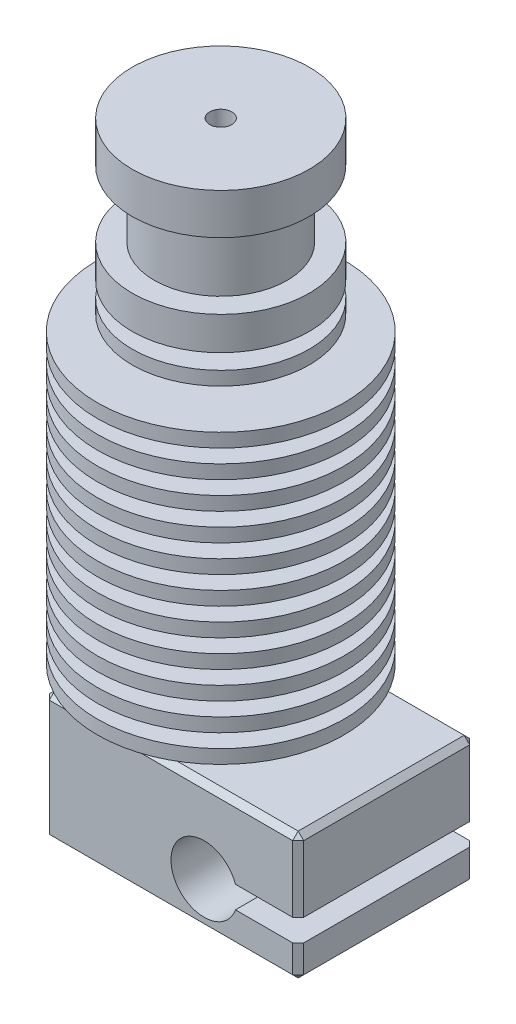
SolidWorks part; units mm, degrees
material "6063-T83"
ref_plane "Front Plane" through (0, 0, 0) normal (0, 0, 1) x (1, 0, 0)
ref_plane "Top Plane" through (0, 0, 0) normal (0, 1, 0) x (1, 0, 0)
ref_plane "Right Plane" through (0, 0, 0) normal (1, 0, 0) x (0, 0, -1)
sketch "Sketch1" plane through (0, 0, 0) normal (0, 0, 1) x (1, 0, 0)
  line L0 (5.8071, 12.7) -> (-2.1929, 12.7)
  line L1 (-2.1929, 12.7) -> (-2.1929, 9)
  line L2 (-2.1929, 9) -> (-0.1929, 9)
  line L3 (-0.1929, 9) -> (-0.1929, 3)
  line L4 (-0.1929, 3) -> (-2.1929, 3)
  line L5 (-2.1929, 3) -> (-2.1929, 0)
  line L6 (-2.1929, 0) -> (1.6177, 0)
  line L7 (1.6177, 0) -> (1.6177, -1.381)
  line L8 (1.6177, -1.381) -> (-2.1929, -1.381)
  line L9 (-2.1929, -1.381) -> (-2.1929, -2.619)
  line L10 (-2.1929, -2.619) -> (1.6177, -2.619)
  line L11 (1.6177, -2.619) -> (1.6177, -4)
  line L12 (1.6177, -4) -> (-5.3429, -4)
  line L13 (-5.3429, -4) -> (-5.3429, -5.2381)
  line L14 (-5.3429, -5.2381) -> (1.6177, -5.2381)
  line L15 (1.6177, -5.2381) -> (1.6177, -6.4762)
  line L16 (1.6177, -6.4762) -> (-5.3429, -6.4762)
  line L17 (-5.3429, -6.4762) -> (-5.3429, -7.7143)
  line L18 (-5.3429, -7.7143) -> (1.6177, -7.7143)
  line L19 (1.6177, -7.7143) -> (1.6177, -8.9524)
  line L20 (1.6177, -8.9524) -> (-5.3429, -8.9524)
  line L21 (-5.3429, -8.9524) -> (-5.3429, -10.1905)
  line L22 (-5.3429, -10.1905) -> (1.6177, -10.1905)
  line L23 (1.6177, -10.1905) -> (1.6177, -11.4286)
  line L24 (1.6177, -11.4286) -> (-5.3429, -11.4286)
  line L25 (-5.3429, -11.4286) -> (-5.3429, -12.6667)
  line L26 (-5.3429, -12.6667) -> (1.6177, -12.6667)
  line L27 (1.6177, -12.6667) -> (1.6177, -13.9048)
  line L28 (1.6177, -13.9048) -> (-5.3429, -13.9048)
  line L29 (-5.3429, -13.9048) -> (-5.3429, -15.1429)
  line L30 (-5.3429, -15.1429) -> (1.6177, -15.1429)
  line L31 (1.6177, -15.1429) -> (1.6177, -16.381)
  line L32 (1.6177, -16.381) -> (-5.3429, -16.381)
  line L33 (-5.3429, -16.381) -> (-5.3429, -17.619)
  line L34 (-5.3429, -17.619) -> (1.6177, -17.619)
  line L35 (1.6177, -17.619) -> (1.6177, -18.8571)
  line L36 (1.6177, -18.8571) -> (-5.3429, -18.8571)
  line L37 (-5.3429, -18.8571) -> (-5.3429, -20.0952)
  line L38 (-5.3429, -20.0952) -> (1.6177, -20.0952)
  line L39 (1.6177, -20.0952) -> (1.6177, -21.3333)
  line L40 (1.6177, -21.3333) -> (-5.3429, -21.3333)
  line L41 (-5.3429, -21.3333) -> (-5.3429, -22.5714)
  line L42 (-5.3429, -22.5714) -> (1.6177, -22.5714)
  line L43 (1.6177, -22.5714) -> (1.6177, -23.8095)
  line L44 (1.6177, -23.8095) -> (-5.3429, -23.8095)
  line L45 (-5.3429, -23.8095) -> (-5.3429, -25.0476)
  line L46 (-5.3429, -25.0476) -> (1.6177, -25.0476)
  line L47 (1.6177, -25.0476) -> (1.6177, -26.2857)
  line L48 (1.6177, -26.2857) -> (-5.3429, -26.2857)
  line L49 (-5.3429, -26.2857) -> (-5.3429, -27.5238)
  line L50 (-5.3429, -27.5238) -> (1.6177, -27.5238)
  line L51 (1.6177, -27.5238) -> (1.6177, -28.7619)
  line L52 (1.6177, -28.7619) -> (-5.3429, -28.7619)
  line L53 (-5.3429, -28.7619) -> (-5.3429, -30)
  line L54 (-5.3429, -30) -> (4.4071, -30)
  line L55 (5.8071, 12.7) -> (5.8071, -23.7672)
  line L56 (4.4071, -30) -> (4.4071, -32.1)
  line L57 (4.4071, -32.1) -> (5.8071, -32.1)
  line L58 (5.8071, -32.1) -> (5.8071, -23.7672)
  dimension "D1" = 26
  dimension "D2" = 42.7
  dimension "D3" = 11.15
  dimension "D4" = 6
  dimension "D5" = 3.7
  dimension "D6" = 3
  dimension "D7" = 1.4
  dimension "D8" = 2.1
  dimension "D9" = 8
  dimension "D10" = 6
revolve "Revolve1" add sketch "Sketch1" angle 360 about L55
sketch "Sketch2" plane through (0, -32.1, 0) normal (0, -1, 0) x (1, 0, 0)
  line L1 (-2.1929, -8) -> (20.8071, -8)
  line L2 (-2.1929, -8) -> (-2.1929, 8)
  line L3 (-2.1929, 8) -> (20.8071, 8)
  line L4 (20.8071, -8) -> (20.8071, 8)
  circle A0 centre (5.8071, 0) radius 1.4 construction
  dimension "D3" = 8
  dimension "D4" = 8
  dimension "D1" = 16
  dimension "D2" = 23
extrude "Boss-Extrude1" add sketch "Sketch2" along normal blind 11.5
sketch "Sketch3" plane through (0, 0, -8) normal (0, 0, -1) x (-1, 0, 0)
  line L0 (2.1929, -43.6) -> (-20.8071, -43.6) construction
  line L1 (2.1929, -43.6) -> (2.1929, -32.1) construction
  line L2 (-20.8071, -43.6) -> (-20.8071, -32.1) construction
  line L3 (-20.8071, -40.6) -> (-12.9233, -40.6)
  line L4 (-20.8071, -40.6) -> (-20.8071, -38.6)
  line L5 (-20.8071, -38.6) -> (-12.9233, -38.6)
  line L6 (-12.9233, -40.6) -> (-12.9233, -38.6)
  circle A0 centre (-12.3071, -39.6) radius 3
  line M6 (-20.8071, -32.1) -> (-20.8071, -43.6)
  dimension "D1" = 4
  dimension "D2" = 14.5
  dimension "D3" = 6
  dimension "D4" = 1
  dimension "D5" = 2
extrude "Cut-Extrude1" cut sketch "Sketch3" against normal blind 21.5 contours A0 L5 L3 M6 | L5 A0 L3 L6 | L3 A0 L5 L6
chamfer "Chamfer1" distance 0.5 angle 45 15 edges at (5.8071, -32.1, 1.4) (9.3071, -43.6, 8) (20.8071, -42.1, 8) (20.8071, -43.6, 0) (9.3071, -43.6, -8) (9.3071, -32.1, -8) (-2.1929, -37.85, 8) (-2.1929, -43.6, 0) (-2.1929, -37.85, -8) (-2.1929, -32.1, 0) (9.3071, -32.1, 8) (20.8071, -35.35, 8) (20.8071, -32.1, 0) (20.8071, -35.35, -8) (20.8071, -42.1, -8)
sketch "Sketch4" plane through (0, 12.7, 0) normal (0, 1, 0) x (1, 0, 0)
  circle A0 centre (5.8071, 0) radius 1
  dimension "D1" = 2
extrude "Cut-Extrude2" cut sketch "Sketch4" against normal blind 56
